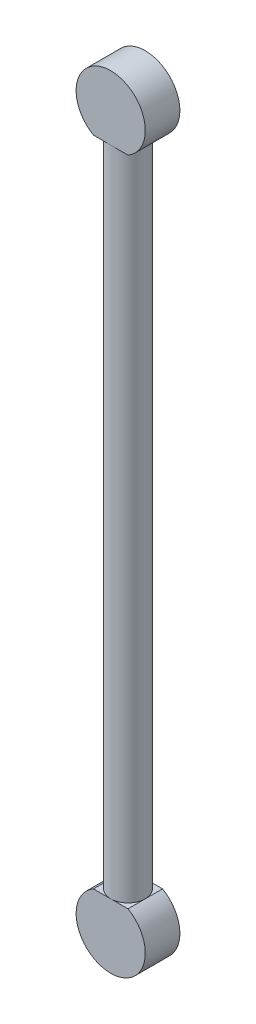
SolidWorks part; units mm, degrees
ref_plane "Front Plane" through (0, 0, 0) normal (0, 0, 1) x (1, 0, 0)
ref_plane "Top Plane" through (0, 0, 0) normal (0, 1, 0) x (1, 0, 0)
ref_plane "Right Plane" through (0, 0, 0) normal (1, 0, 0) x (0, 0, -1)
sketch "Sketch1" plane through (0, 0, 0) normal (0, 1, 0) x (1, 0, 0)
  circle A0 centre (0, 0) radius 3.175
  dimension "D1" = 6.35
extrude "center rod" add sketch "Sketch1" along normal blind 119.888
sketch "Sketch2" plane through (0, 0, 0) normal (0, 0, 1) x (1, 0, 0)
  line L0 (0, 119.888) -> (0, 131.7373) construction
  line L1 (3.175, 119.888) -> (-3.175, 119.888) construction
  line L2 (-3.175, 119.888) -> (3.175, 119.888)
  line L3 (3.175, 59.944) -> (-3.175, 59.944) construction
  line L4 (3.175, 0) -> (3.175, 119.888) construction
  line L5 (-3.175, 119.888) -> (-3.175, 0) construction
  line L6 (0, 0) -> (0, -11.8493) construction
  line L7 (-3.175, 0) -> (3.175, 0)
  arc A0 (-3.175, 119.888) -> (3.175, 119.888) centre (0, 125.3873) cw
  arc A1 (-3.175, 0) -> (3.175, 0) centre (0, -5.4993) ccw
  point P9 (0, 131.7373)
  dimension "D1" = 6.35
extrude "circle ends" add sketch "Sketch2" along normal mid plane 6.35
sketch "Sketch3" plane through (0, 0, 3.175) normal (0, 0, 1) x (1, 0, 0)
  point P0 (0, -5.4993)
  point P1 (0, 125.3873)
  point P2 (0, 0)
  point P3 (1.382, -4.3697)
  point P4 (0, 0)
  point P6 (0, 0)
sketch "Sketch4" plane through (0, 0, -3.175) normal (0, 0, -1) x (-1, 0, 0)
  point P0 (0, 125.3873)
  point P1 (0, -5.4993)
